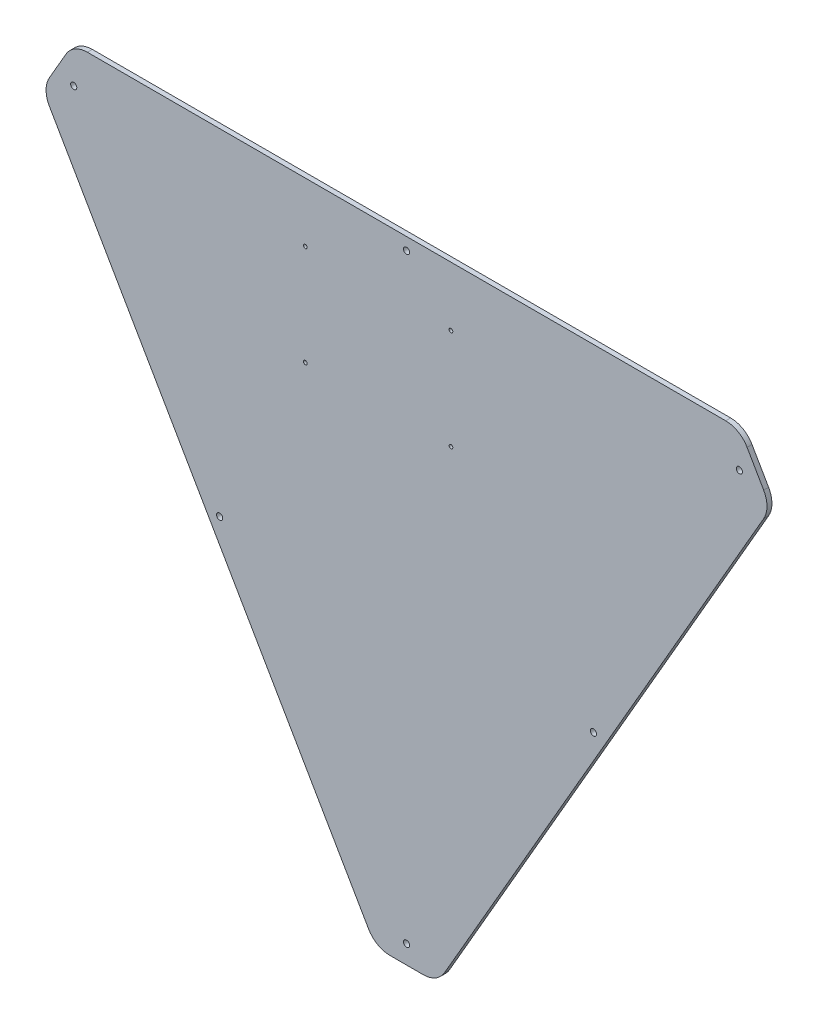
SolidWorks part; units mm, degrees
ref_plane "Piano frontale" through (0, 0, 0) normal (0, 0, 1) x (1, 0, 0)
ref_plane "Piano superiore" through (0, 0, 0) normal (0, 1, 0) x (1, 0, 0)
ref_plane "Piano destro" through (0, 0, 0) normal (1, 0, 0) x (0, 0, -1)
sketch "Schizzo1" plane through (0, 0, 0) normal (0, 0, 1) x (1, 0, 0)
  line L12 (69.543, -257.1703) -> (65.2129, -264.6703)
  line L13 (47.8924, -274.6703) -> (20.9864, -274.6703)
  line L14 (3.6659, -264.6703) -> (-0.6642, -257.1703)
  line L15 (-0.6642, -257.1703) -> (-250.6642, 175.8424)
  line L16 (-250.6642, 175.8424) -> (-254.9944, 183.3424)
  line L17 (-254.9944, 203.3424) -> (-241.5414, 226.6436)
  line L18 (-224.2209, 236.6436) -> (-215.5606, 236.6436)
  line L19 (284.4394, 236.6436) -> (-215.5606, 236.6436)
  line L20 (69.543, -257.1703) -> (319.543, 175.8424)
  line L21 (323.8731, 183.3424) -> (319.543, 175.8424)
  line L22 (310.4202, 226.6436) -> (323.8731, 203.3424)
  line L23 (284.4394, 236.6436) -> (293.0996, 236.6436)
  arc A6 (47.8924, -274.6703) -> (65.2129, -264.6703) centre (47.8924, -254.6703) ccw
  arc A7 (3.6659, -264.6703) -> (20.9864, -274.6703) centre (20.9864, -254.6703) ccw
  arc A8 (-254.9944, 203.3424) -> (-254.9944, 183.3424) centre (-237.6739, 193.3424) ccw
  arc A9 (-224.2209, 236.6436) -> (-241.5414, 226.6436) centre (-224.2209, 216.6436) ccw
  arc A10 (323.8731, 183.3424) -> (323.8731, 203.3424) centre (306.5526, 193.3424) ccw
  arc A11 (310.4202, 226.6436) -> (293.0996, 236.6436) centre (293.0996, 216.6436) ccw
  circle A15 centre (34.4394, -259.6703) radius 2.1
  circle A16 centre (304.1563, 207.493) radius 2.1
  circle A17 centre (-235.2775, 207.493) radius 2.1
extrude "Estrusione-Estrusione1" add sketch "Schizzo1" along normal blind 4
sketch "Schizzo2" plane through (0, 0, 4) normal (0, 0, 1) x (1, 0, 0)
  line L0 (-224.2209, 226.6436) -> (293.0996, 226.6436) construction
  line L1 (293.0996, 236.6436) -> (-224.2209, 236.6436) construction
  line L2 (34.4394, 236.6436) -> (34.4394, -274.6703) construction
  line L3 (20.9864, -274.6703) -> (47.8924, -274.6703) construction
  line L4 (-125.6642, -40.664) -> (317.1467, 214.993) construction
  line L5 (-254.9944, 183.3424) -> (3.6659, -264.6703) construction
  line L6 (323.8731, 203.3424) -> (310.4202, 226.6436) construction
  line L7 (315.2129, 188.3424) -> (56.5526, -259.6703) construction
  line L8 (12.3261, -259.6703) -> (-246.3341, 188.3424) construction
  circle A0 centre (34.4394, 226.6436) radius 2.5
  circle A1 centre (-235.2775, 207.493) radius 2.5
  circle A2 centre (304.1563, 207.493) radius 2.5
  circle A3 centre (34.4394, -259.6703) radius 2.5
  circle A4 centre (185.8828, -35.664) radius 2.5
  circle A5 centre (-117.004, -35.664) radius 2.5
  point P16 (34.4394, 51.7719)
  point P17 (34.4394, 226.6436)
  point P40 (34.4394, 51.7719)
  dimension "D2" = 5
  dimension "D3" = 5
  dimension "D1" = 10
  dimension "D4" = 3
extrude "Taglio-Estrusione1" cut sketch "Schizzo2" against normal blind 4
sketch "Schizzo3" plane through (0, 0, 4) normal (0, 0, 1) x (1, 0, 0)
  line L0 (293.0996, 236.6436) -> (-224.2209, 236.6436) construction
  line L1 (-64.5606, 99.1436) -> (133.4394, 99.1436) construction
  line L2 (-64.5606, 99.1436) -> (-64.5606, 196.6436) construction
  line L3 (-64.5606, 196.6436) -> (133.4394, 196.6436) construction
  line L4 (133.4394, 99.1436) -> (133.4394, 196.6436) construction
  line L5 (-64.5606, 99.1436) -> (133.4394, 196.6436) construction
  line L6 (-64.5606, 196.6436) -> (133.4394, 99.1436) construction
  line L7 (34.4394, 236.6436) -> (34.4394, -274.6703) construction
  line L8 (20.9864, -274.6703) -> (47.8924, -274.6703) construction
  line L9 (-47.5606, 107.1436) -> (70.4394, 107.1436) construction
  line L10 (133.4394, 147.8936) -> (-64.5606, 147.8936) construction
  line L11 (-47.5606, 188.6436) -> (70.4394, 188.6436) construction
  circle A0 centre (-47.5606, 107.1436) radius 1.5
  circle A1 centre (70.4394, 107.1436) radius 1.5
  circle A2 centre (-47.5606, 188.6436) radius 1.5
  circle A3 centre (70.4394, 188.6436) radius 1.5
  point P0 (34.4394, 147.8936)
  dimension "D6" = 3
  dimension "D1" = 97.5
  dimension "D2" = 198
  dimension "D3" = 40
  dimension "D4" = 118
  dimension "D5" = 8
  dimension "D7" = 17
extrude "Taglio-Estrusione3" cut sketch "Schizzo3" against normal blind 4
